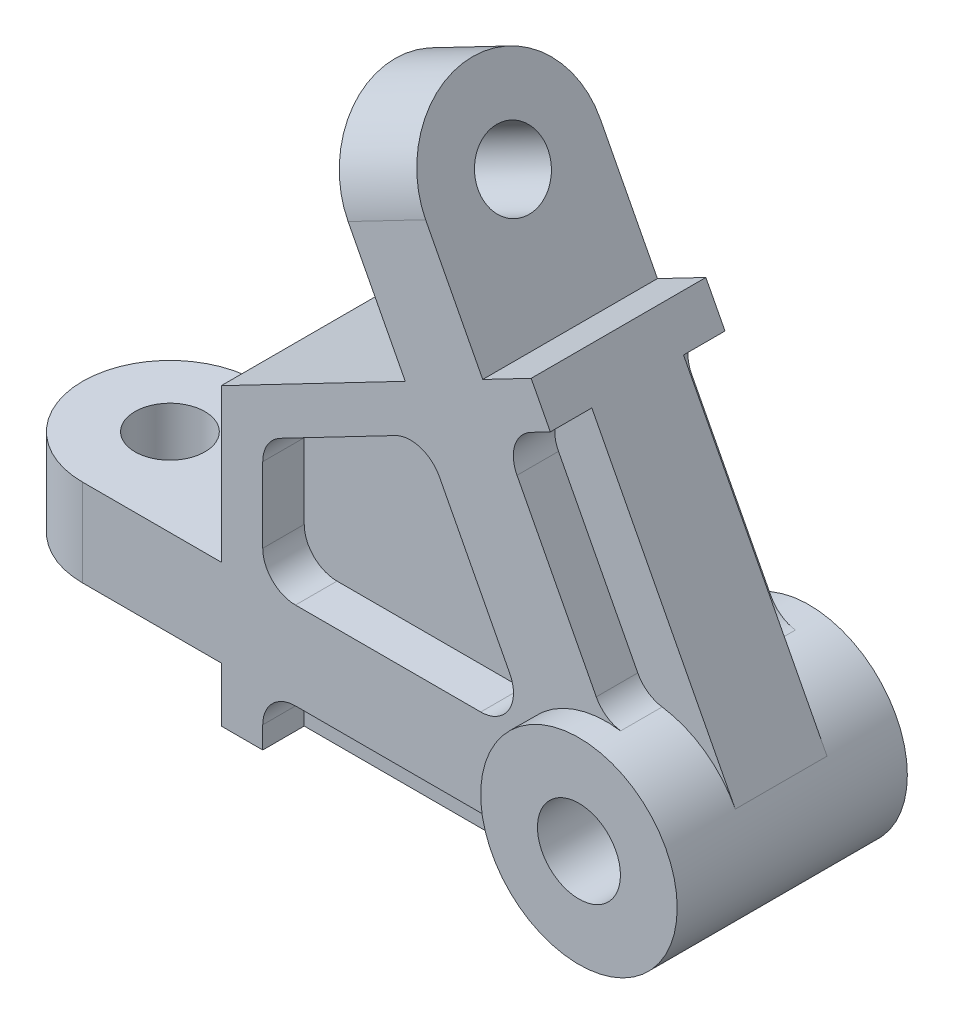
SolidWorks part; units mm, degrees
material "Alliage 1060"
ref_plane "Plan de face" through (0, 0, 0) normal (0, 0, 1) x (1, 0, 0)
ref_plane "Plan de dessus" through (0, 0, 0) normal (0, 1, 0) x (1, 0, 0)
ref_plane "Plan de droite" through (0, 0, 0) normal (1, 0, 0) x (0, 0, -1)
sketch "Esquisse1" plane through (0, 0, 0) normal (0, 0, 1) x (1, 0, 0)
  line L0 (19.9577, 10.3893) -> (-17.2891, 81.9399)
  line L1 (0, -22.5) -> (-88.25, -22.5)
  line L2 (-88.25, -22.5) -> (-88.25, -10)
  line L3 (-88.25, -10) -> (-140, -10)
  line L4 (-140, -10) -> (-140, 10)
  line L5 (-140, 10) -> (-88.25, 10)
  line L6 (-88.25, 10) -> (-88.25, 45)
  line L7 (-88.25, 45) -> (-46.117, 66.9331)
  line L8 (-46.117, 66.9331) -> (-68.4357, 109.8069)
  line L9 (-68.4357, 109.8069) -> (-50.6955, 119.0419)
  line L10 (-50.6955, 119.0419) -> (-28.3768, 76.168)
  line L11 (-28.3768, 76.168) -> (-17.2891, 81.9399)
  line L12 (0, 0) -> (-59.5656, 114.4244) construction
  line L13 (0, 0) -> (-140, 0) construction
  circle A0 centre (0, 0) radius 22.5
  circle A1 centre (0, 0) radius 9.5
  dimension "D1" = 45
  dimension "D2" = 19
  dimension "D3" = 20
  dimension "D4" = 20
  dimension "D5" = 35
  dimension "D6" = 140
  dimension "D7" = 51.75
  dimension "D9" = 62.5
  dimension "D8" = 129
extrude "Boss.-Extru.1" add sketch "Esquisse1" along normal blind 40 contours A0 L0 L11 L10 L9 L8 L7 L6 L5 L4 L3 L2 L1 | A0 A1
sketch "Esquisse2" plane through (0, 0, 40) normal (0, 0, 1) x (1, 0, 0)
  line L0 (0, -22.5) -> (-88.25, -22.5) construction
  line L1 (-88.25, -22.5) -> (-88.25, -10) construction
  line L2 (-88.25, -10) -> (-140, -10) construction
  line L3 (-140, -10) -> (-140, 10) construction
  line L4 (-140, 10) -> (-88.25, 10) construction
  line L5 (-88.25, 10) -> (-88.25, 45) construction
  line L6 (-88.25, 45) -> (-46.117, 66.9331) construction
  line L7 (-46.117, 66.9331) -> (-68.4357, 109.8069) construction
  line L8 (-68.4357, 109.8069) -> (-50.6955, 119.0419) construction
  line L9 (-50.6955, 119.0419) -> (-28.3768, 76.168) construction
  line L10 (-28.3768, 76.168) -> (-17.2891, 81.9399) construction
  line L11 (19.9577, 10.3893) -> (-17.2891, 81.9399) construction
  line L12 (0, -22.5) -> (-88.25, -22.5)
  line L13 (-88.25, -22.5) -> (-88.25, -10)
  line L14 (-88.25, -10) -> (-140, -10)
  line L15 (-140, -10) -> (-140, 10)
  line L16 (-140, 10) -> (-88.25, 10)
  line L17 (-88.25, 10) -> (-88.25, 45)
  line L18 (-88.25, 45) -> (-46.117, 66.9331)
  line L19 (-46.117, 66.9331) -> (-68.4357, 109.8069)
  line L20 (-68.4357, 109.8069) -> (-50.6955, 119.0419)
  line L21 (-50.6955, 119.0419) -> (-28.3768, 76.168)
  line L22 (-28.3768, 76.168) -> (-17.2891, 81.9399)
  line L23 (19.9577, 10.3893) -> (-17.2891, 81.9399)
  circle A1 centre (0, 0) radius 9.5
  circle A2 centre (0, 0) radius 9.5
  circle A3 centre (0, 0) radius 22.5
  circle A4 centre (0, 0) radius 22.5
  arc M4 (0, -22.5) -> (19.9577, 10.3893) centre (0, 0) ccw
  circle M16 centre (0, 0) radius 9.5
  dimension "D1" = 0
  dimension "D2" = 0
extrude "Boss.-Extru.2" add sketch "Esquisse2" along normal blind 6.35 and the other way blind 46.35 contours A4 M4 M16
sketch "Esquisse3" plane through (8.8701, 4.6175, 0) normal (0.887, 0.4617, 0) x (0, 0, -1)
  line L0 (-40, 129) -> (-40, 109) construction
  line L1 (-40, 129) -> (-40, 80.6648) construction
  line L2 (-40, 109) -> (-20, 109) construction
  line L3 (0, 129) -> (0, 80.6648) construction
  line L5 (0, 9.5) -> (0, -9.5)
  line L6 (0, 9.5) -> (0, -9.5)
  line L7 (0, 22.5) -> (0, -22.5)
  line L8 (0, 80.6648) -> (0, 129)
  line L9 (0, 129) -> (-40, 129)
  line L10 (-40, 129) -> (-40, 80.6648)
  line L11 (-40, 80.6648) -> (0, 80.6648)
  line L12 (0, 80.6648) -> (0, 129)
  line L13 (0, 129) -> (-40, 129)
  line L14 (-40, 129) -> (-40, 80.6648)
  line L15 (-40, 80.6648) -> (0, 80.6648)
  line L16 (0, 22.5) -> (0, -22.5)
  line L22 (-46.35, 9.5) -> (-46.35, -9.5) construction
  line L23 (-46.35, 9.5) -> (-46.35, -9.5)
  arc A0 (-40, 109) -> (0, 109) centre (-20, 109) cw
  circle A1 centre (-20, 109) radius 8
  line M7 (0, 129) -> (-40, 129)
  line M8 (-40, 129) -> (-40, 80.6648)
  dimension "D1" = 20
  dimension "D3" = 109
  dimension "D2" = 0
  dimension "D4" = 0
  dimension "D5" = 0
extrude "Enlèv. mat.-Extru.1" cut sketch "Esquisse3" against normal through all contours A0 L12 M7 | A0 L13 M8 | A1
sketch "Esquisse4" plane through (0, 10, 0) normal (0, 1, 0) x (1, 0, 0)
  line L0 (-140, -40) -> (-120, -40) construction
  line L1 (-140, -40) -> (-88.25, -40) construction
  line L2 (-120, -40) -> (-120, -20) construction
  line L3 (-140, 0) -> (-88.25, 0) construction
  line L8 (-88.25, 0) -> (-140, 0)
  line L9 (-140, 0) -> (-140, -40)
  line L10 (-140, -40) -> (-88.25, -40)
  line L11 (-88.25, -40) -> (-88.25, 0)
  line L12 (-88.25, 0) -> (-140, 0)
  line L14 (-140, -40) -> (-88.25, -40)
  line L15 (-88.25, -40) -> (-88.25, 0)
  line L17 (-140, 0) -> (-140, -40)
  circle A0 centre (-120, -20) radius 8
  arc A1 (-120, -40) -> (-120, 0) centre (-120, -20) cw
  line M8 (-140, 0) -> (-140, -40)
  line M9 (-140, -40) -> (-88.25, -40)
  dimension "D1" = 0
  dimension "D2" = 120
extrude "Enlèv. mat.-Extru.2" cut sketch "Esquisse4" against normal through all contours A0 | A1 L12 M8 | A1 L17 M9
sketch "Esquisse5" plane through (0, 0, 40) normal (0, 0, 1) x (1, 0, 0)
  line L0 (-24.367, -10) -> (-71.25, -10)
  line L1 (-78.75, -17.5) -> (-78.75, -22.5)
  line L2 (0, -22.5) -> (-88.25, -22.5) construction
  line L3 (0, -22.5) -> (-88.25, -22.5) construction
  line L4 (-88.25, -22.5) -> (-88.25, -10) construction
  line L5 (-88.25, -10) -> (-140, -10) construction
  line L6 (-140, -10) -> (-140, 10) construction
  line L7 (-140, 10) -> (-88.25, 10) construction
  line L8 (-88.25, 10) -> (-88.25, 45) construction
  line L9 (-88.25, 45) -> (-46.117, 66.9331) construction
  line L10 (-46.117, 66.9331) -> (-68.4357, 109.8069) construction
  line L11 (-68.4357, 109.8069) -> (-50.6955, 119.0419) construction
  line L12 (-50.6955, 119.0419) -> (-28.3768, 76.168) construction
  line L13 (-28.3768, 76.168) -> (-17.2891, 81.9399) construction
  line L14 (19.9577, 10.3893) -> (-17.2891, 81.9399) construction
  line L15 (0, -22.5) -> (-88.25, -22.5)
  line L16 (-88.25, -22.5) -> (-88.25, -10)
  line L17 (-88.25, -10) -> (-140, -10)
  line L18 (-140, -10) -> (-140, 10)
  line L19 (-140, 10) -> (-88.25, 10)
  line L20 (-88.25, 10) -> (-88.25, 45)
  line L21 (-88.25, 45) -> (-46.117, 66.9331)
  line L22 (-46.117, 66.9331) -> (-68.4357, 109.8069)
  line L23 (-68.4357, 109.8069) -> (-50.6955, 119.0419)
  line L24 (-50.6955, 119.0419) -> (-28.3768, 76.168)
  line L25 (-28.3768, 76.168) -> (-17.2891, 81.9399)
  line L26 (19.9577, 10.3893) -> (-17.2891, 81.9399)
  line L27 (0, -22.5) -> (-88.25, -22.5)
  line L28 (-88.25, -22.5) -> (-88.25, -10)
  line L29 (-88.25, -10) -> (-140, -10)
  line L30 (-140, -10) -> (-140, 10)
  line L31 (-140, 10) -> (-88.25, 10)
  line L32 (-88.25, 10) -> (-88.25, 45)
  line L33 (-88.25, 45) -> (-46.117, 66.9331)
  line L34 (-46.117, 66.9331) -> (-68.4357, 109.8069)
  line L35 (-68.4357, 109.8069) -> (-50.6955, 119.0419)
  line L36 (-50.6955, 119.0419) -> (-28.3768, 76.168)
  line L37 (-28.3768, 76.168) -> (-17.2891, 81.9399)
  line L38 (19.9577, 10.3893) -> (-17.2891, 81.9399)
  line L39 (0, 0) -> (-140, 0) construction
  line L40 (0, 0) -> (-67.6924, 130.0359) construction
  line L41 (-2.3813, 26.2313) -> (-20.527, 61.0889)
  line L42 (-17.3376, 71.2046) -> (-12.9025, 73.5133)
  line L43 (-74.7131, 41.3367) -> (-48.3829, 55.0434)
  line L44 (-78.75, 17.5) -> (-78.75, 34.6841)
  line L45 (-38.2672, 51.8539) -> (-22.1865, 20.9631)
  line L46 (-78.75, 10) -> (-78.75, 45) construction
  line L47 (-83.8634, 36.5734) -> (-41.7304, 58.5065) construction
  line L48 (-28.8391, 10) -> (-71.25, 10)
  circle A0 centre (0, 0) radius 22.5 construction
  arc A1 (-71.25, -10) -> (-78.75, -17.5) centre (-71.25, -17.5) ccw
  arc A2 (19.9577, 10.3893) -> (0, -22.5) centre (0, 0) ccw construction
  arc A3 (-18.2752, -13.125) -> (0, -22.5) centre (0, 0) ccw
  arc A4 (-24.367, -10) -> (-18.2752, -13.125) centre (-24.367, -17.5) cw
  arc A5 (-20.527, 61.0889) -> (-17.3376, 71.2046) centre (-13.8744, 64.552) cw
  circle A6 centre (0, 0) radius 9.5
  circle A7 centre (0, 0) radius 9.5
  circle A8 centre (0, 0) radius 22.5
  arc A9 (-10.3893, 19.9577) -> (3.2035, 22.2708) centre (0, 0) ccw
  arc A10 (-2.3813, 26.2313) -> (3.2035, 22.2708) centre (4.2713, 29.6944) ccw
  arc A11 (-78.75, 34.6841) -> (-74.7131, 41.3367) centre (-71.25, 34.6841) cw
  arc A12 (-22.1865, 20.9631) -> (-28.8391, 10) centre (-28.8391, 17.5) cw
  arc A13 (-48.3829, 55.0434) -> (-38.2672, 51.8539) centre (-44.9198, 48.3908) cw
  arc A14 (-78.75, 17.5) -> (-71.25, 10) centre (-71.25, 17.5) ccw
  point P14 (-20.1556, -10)
  point P41 (-0.4367, 22.4958)
  point P58 (-203.1551, 55.0896)
  line M28 (-88.25, -22.5) -> (0, -22.5)
  arc M29 (0, -22.5) -> (19.9577, 10.3893) centre (0, 0) cw
  line M30 (19.9577, 10.3893) -> (-17.2891, 81.9399)
  dimension "D1" = 7.5
  dimension "D2" = 7.5
  dimension "D5" = 7.5
  dimension "D9" = 7.5
  dimension "D10" = 7.5
  dimension "D11" = 7.5
  dimension "D12" = 7.5
  dimension "D6" = 9.5
  dimension "D7" = 9.5
  dimension "D3" = 0
  dimension "D4" = 0
  dimension "D8" = 9.5
extrude "Enlèv. mat.-Extru.3" cut sketch "Esquisse5" against normal blind 9.5 contours A4 L0 A1 L1 M28 M29 | L41 A10 L42 A5 M29 M30 | L44 A14 L48 A12 L45 A13 L43 A11
ref_plane "Plan1" through (0, 0, 20) normal (0, 0, -1) x (-1, 0, 0)
mirror "Symétrie1" about plane through (0, 0, 20) normal (0, 0, -1) of "Enlèv. mat.-Extru.3"
equation "\"A\" = 109"
equation "\"B\"= 20"
equation "\"C\"= 62.5"
equation "\"D3@Esquisse1\"=\"B\""
equation "\"D4@Esquisse1\"=\"B\""
equation "\"D9@Esquisse1\"=\"C\""
equation "\"D8@Esquisse1\"=\"A\"+20"
equation "\"D3@Esquisse3\"=\"A\""
